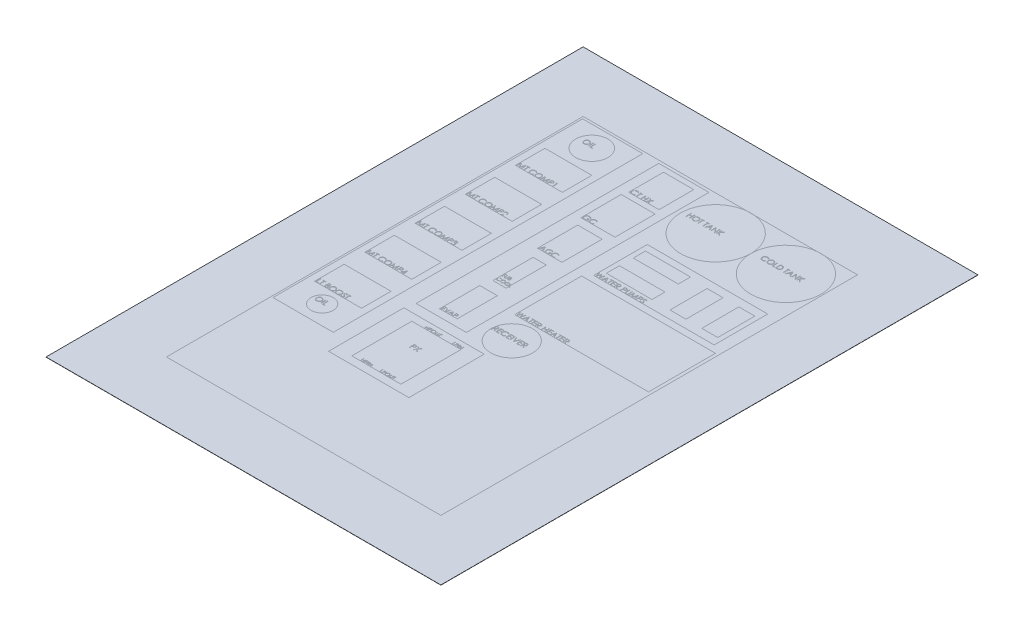
SolidWorks part; units mm, degrees
ref_plane "Front Plane" through (0, 0, 0) normal (0, 0, 1) x (1, 0, 0)
ref_plane "Top Plane" through (0, 0, 0) normal (0, 1, 0) x (1, 0, 0)
ref_plane "Right Plane" through (0, 0, 0) normal (1, 0, 0) x (0, 0, -1)
sketch "Sketch1" plane through (0, 0, 0) normal (0, 1, 0) x (1, 0, 0)
  line L1 (2997.2, 4076.7) -> (-2997.2, 4076.7)
  line L2 (2997.2, 4076.7) -> (2997.2, -4076.7)
  line L3 (2997.2, -4076.7) -> (-2997.2, -4076.7)
  line L4 (-2997.2, 4076.7) -> (-2997.2, -4076.7)
  line L5 (0, -4076.7) -> (0, 4076.7) construction
  line L6 (2997.2, 0) -> (-2997.2, 0) construction
  point P0 (0, 0)
  dimension "D1" = 5994.4
  dimension "D2" = 8153.4
extrude "Boss-Extrude1" add sketch "Sketch1" against normal blind 2.54
sketch "Sketch2" plane through (0, 0, 0) normal (0, 1, 0) x (1, 0, 0)
  line L0 (-2997.2, -4076.7) -> (2997.2, -4076.7) construction
  line L1 (-2082.8, 3162.3) -> (2082.8, 3162.3)
  line L2 (-2082.8, 3162.3) -> (-2082.8, -3162.3)
  line L3 (-2082.8, -3162.3) -> (2082.8, -3162.3)
  line L4 (2082.8, 3162.3) -> (2082.8, -3162.3)
  line L5 (0, -3162.3) -> (0, 3162.3) construction
  line L6 (-2082.8, 0) -> (2082.8, 0) construction
  line L7 (-2997.2, 4076.7) -> (-2997.2, -4076.7) construction
  point P0 (0, 0)
  dimension "D1" = 914.4
  dimension "D2" = 914.4
split line "Split Line1"
sketch "Sketch3" plane through (0, 0, 0) normal (0, 1, 0) x (1, 0, 0)
  line L0 (-1953.5274, 1244.4006) -> (-1242.3274, 1244.4006)
  line L1 (-2055.1274, 3126.5428) -> (-1140.7274, 3126.5428)
  line L2 (-2055.1274, 3126.5428) -> (-2055.1274, -1572.4572)
  line L3 (-2055.1274, -1572.4572) -> (-1140.7274, -1572.4572)
  line L4 (-1140.7274, 3126.5428) -> (-1140.7274, -1572.4572)
  line L5 (-1597.9274, -1572.4572) -> (-1597.9274, 3126.5428) construction
  line L6 (-2055.1274, 777.0428) -> (-1140.7274, 777.0428) construction
  line L7 (-1953.5274, 2006.4006) -> (-1242.3274, 2006.4006)
  line L8 (-1953.5274, 2006.4006) -> (-1953.5274, 2453.4406)
  line L9 (-1953.5274, 2453.4406) -> (-1242.3274, 2453.4406)
  line L10 (-1242.3274, 2006.4006) -> (-1242.3274, 2453.4406)
  line L11 (-1597.9274, 2453.4406) -> (-1597.9274, 2006.4006) construction
  line L12 (-1953.5274, 2229.9206) -> (-1242.3274, 2229.9206) construction
  line L13 (-1242.3274, 1244.4006) -> (-1242.3274, 1691.4406)
  line L14 (-1953.5274, 1691.4406) -> (-1242.3274, 1691.4406)
  line L15 (-1953.5274, 1244.4006) -> (-1953.5274, 1691.4406)
  line L16 (-1953.5274, 482.4006) -> (-1242.3274, 482.4006)
  line L17 (-1242.3274, 482.4006) -> (-1242.3274, 929.4406)
  line L18 (-1953.5274, 929.4406) -> (-1242.3274, 929.4406)
  line L19 (-1953.5274, 482.4006) -> (-1953.5274, 929.4406)
  line L20 (-1953.5274, -279.5994) -> (-1242.3274, -279.5994)
  line L21 (-1242.3274, -279.5994) -> (-1242.3274, 167.4406)
  line L22 (-1953.5274, 167.4406) -> (-1242.3274, 167.4406)
  line L23 (-1953.5274, -279.5994) -> (-1953.5274, 167.4406)
  line L24 (-1953.5274, -1041.5994) -> (-1242.3274, -1041.5994)
  line L29 (-927.3956, -713.9777) -> (291.8044, -713.9777)
  line L30 (-927.3956, -713.9777) -> (-927.3956, -1856.9777)
  line L35 (0, 4076.7) -> (0, -4076.7) construction
  line L36 (2387.6, 0) -> (-2387.6, 0) construction
  line L37 (-927.3956, -1856.9777) -> (291.8044, -1856.9777)
  line L38 (291.8044, -713.9777) -> (291.8044, -1856.9777)
  line L39 (-317.7956, -1856.9777) -> (-317.7956, -713.9777) construction
  line L40 (-927.3956, -1285.4777) -> (291.8044, -1285.4777) construction
  line L41 (-891.0895, 3118.7654) -> (-129.0895, 3118.7654)
  line L42 (-891.0895, 3118.7654) -> (-891.0895, -564.2346)
  line L43 (-891.0895, -564.2346) -> (-129.0895, -564.2346)
  line L44 (-129.0895, 3118.7654) -> (-129.0895, -564.2346)
  line L45 (-510.0895, -564.2346) -> (-510.0895, 3118.7654) construction
  line L46 (-891.0895, 1277.2654) -> (-129.0895, 1277.2654) construction
  line L47 (-1242.3274, -1041.5994) -> (-1242.3274, -594.5594)
  line L48 (87.4738, 1965.4605) -> (1916.2738, 1965.4605)
  line L49 (87.4738, 1965.4605) -> (87.4738, 1152.6605)
  line L50 (87.4738, 1152.6605) -> (1916.2738, 1152.6605)
  line L51 (1916.2738, 1965.4605) -> (1916.2738, 1152.6605)
  line L52 (1001.8738, 1152.6605) -> (1001.8738, 1965.4605) construction
  line L53 (87.4738, 1559.0605) -> (1916.2738, 1559.0605) construction
  line L58 (-376.8877, -1193.0963) -> (-157.3231, -1193.0963) construction
  line L59 (159.8564, 1866.0856) -> (843.3441, 1866.0856)
  line L60 (-1953.5274, -594.5594) -> (-1242.3274, -594.5594)
  line L61 (-1953.5274, -1041.5994) -> (-1953.5274, -594.5594)
  line L62 (459.9911, 2631.5365) -> (1526.7911, 2631.5365) construction
  line L64 (3.5213, 1053.0045) -> (2035.5213, 1053.0045)
  line L65 (3.5213, 1053.0045) -> (3.5213, 37.0045)
  line L66 (3.5213, 37.0045) -> (2035.5213, 37.0045)
  line L67 (2035.5213, 1053.0045) -> (2035.5213, 37.0045)
  line L68 (1019.5213, 37.0045) -> (1019.5213, 1053.0045) construction
  line L69 (3.5213, 545.0045) -> (2035.5213, 545.0045) construction
  line L70 (-739.499, 2512.3519) -> (-280.68, 2512.3519)
  line L71 (-739.499, 2512.3519) -> (-739.499, 3039.5984)
  line L72 (-739.499, 3039.5984) -> (-280.68, 3039.5984)
  line L73 (-280.68, 2512.3519) -> (-280.68, 3039.5984)
  line L74 (-510.0895, 3039.5984) -> (-510.0895, 2512.3519) construction
  line L75 (-739.499, 2775.9751) -> (-280.68, 2775.9751) construction
  line L76 (-767.4761, 1815.7784) -> (-252.7028, 1815.7784)
  line L77 (-767.4761, 1815.7784) -> (-767.4761, 2425.3784)
  line L78 (-767.4761, 2425.3784) -> (-252.7028, 2425.3784)
  line L79 (-252.7028, 1815.7784) -> (-252.7028, 2425.3784)
  line L80 (-510.0895, 2425.3784) -> (-510.0895, 1815.7784) construction
  line L81 (-767.4761, 2120.5784) -> (-252.7028, 2120.5784) construction
  line L82 (-695.4774, 1083.3993) -> (-324.7016, 1083.3993)
  line L83 (-695.4774, 1083.3993) -> (-695.4774, 1692.9993)
  line L84 (-695.4774, 1692.9993) -> (-324.7016, 1692.9993)
  line L85 (-324.7016, 1083.3993) -> (-324.7016, 1692.9993)
  line L86 (-510.0895, 1692.9993) -> (-510.0895, 1083.3993) construction
  line L87 (-695.4774, 1388.1993) -> (-324.7016, 1388.1993) construction
  line L88 (-610.5235, 320.3017) -> (-409.6555, 320.3017)
  line L89 (-610.5235, 320.3017) -> (-610.5235, 929.9017)
  line L90 (-610.5235, 929.9017) -> (-409.6555, 929.9017)
  line L91 (-409.6555, 320.3017) -> (-409.6555, 929.9017)
  line L92 (-510.0895, 929.9017) -> (-510.0895, 320.3017) construction
  line L93 (-610.5235, 625.1017) -> (-409.6555, 625.1017) construction
  line L94 (-643.2912, -454.8388) -> (-376.8877, -454.8388)
  line L95 (-643.2912, -454.8388) -> (-643.2912, 154.7612)
  line L96 (-643.2912, 154.7612) -> (-376.8877, 154.7612)
  line L97 (-376.8877, -454.8388) -> (-376.8877, 154.7612)
  line L98 (-510.0895, 154.7612) -> (-510.0895, -454.8388) construction
  line L99 (-643.2912, -150.0388) -> (-376.8877, -150.0388) construction
  line L104 (159.8564, 1866.0856) -> (159.8564, 1680.7179)
  line L105 (155.8267, 1559.0605) -> (397.9781, 1559.0605) construction
  line L109 (1363.1781, 1840.8555) -> (1363.1781, 1277.2654)
  line L110 (1121.0267, 1840.8555) -> (1363.1781, 1840.8555)
  line L111 (1121.0267, 1840.8555) -> (1121.0267, 1277.2654)
  line L112 (1121.0267, 1277.2654) -> (1363.1781, 1277.2654)
  line L113 (1845.7781, 1840.8555) -> (1845.7781, 1277.2654)
  line L114 (1603.6267, 1840.8555) -> (1845.7781, 1840.8555)
  line L115 (1603.6267, 1840.8555) -> (1603.6267, 1277.2654)
  line L116 (1603.6267, 1277.2654) -> (1845.7781, 1277.2654)
  line L117 (159.8564, 1680.7179) -> (843.3441, 1680.7179)
  line L118 (-1762.7379, 2809.6251) -> (-1419.3839, 2809.6251) construction
  line L119 (-1728.5181, -1284.3926) -> (-1493.1188, -1284.3926) construction
  line L120 (8.1371, -329.3426) -> (643.1371, -329.3426) construction
  line L121 (0, 2631.5365) -> (459.9911, 2631.5365) construction
  line L122 (1121.0267, 2631.5365) -> (1845.7781, 2631.5365) construction
  line L123 (843.3441, 1866.0856) -> (843.3441, 1680.7179)
  line L124 (55.0486, -1740.9553) -> (-690.6399, -1740.9553)
  line L125 (55.0486, -1740.9553) -> (55.0486, -830.0002)
  line L126 (55.0486, -830.0002) -> (-690.6399, -830.0002)
  line L127 (-690.6399, -1740.9553) -> (-690.6399, -830.0002)
  line L128 (-317.7956, -830.0002) -> (-317.7956, -1740.9553) construction
  line L129 (55.0486, -1285.4777) -> (-690.6399, -1285.4777) construction
  line L134 (501.6003, 1680.7179) -> (501.6003, 1866.0856) construction
  line L135 (159.8564, 1773.4018) -> (843.3441, 1773.4018) construction
  line L136 (155.8267, 1475.2016) -> (847.3738, 1475.2016)
  line L137 (155.8267, 1475.2016) -> (155.8267, 1277.2654)
  line L138 (155.8267, 1277.2654) -> (847.3738, 1277.2654)
  line L139 (847.3738, 1475.2016) -> (847.3738, 1277.2654)
  line L140 (501.6003, 1277.2654) -> (501.6003, 1475.2016) construction
  line L141 (155.8267, 1376.2335) -> (847.3738, 1376.2335) construction
  circle A0 centre (325.6371, -329.3426) radius 317.5
  circle A1 centre (1526.7911, 2631.5365) radius 533.4
  circle A2 centre (459.9911, 2631.5365) radius 533.4
  circle A3 centre (-1597.9274, 2809.6251) radius 244.3696
  circle A4 centre (-1597.9274, -1284.3926) radius 168.3871
  text T0 "MT COMP1" font "Century Gothic" height in points 300
  text T1 "MT COMP2" font "Century Gothic" height in points 300
  text T2 "MT COMP3" font "Century Gothic" height in points 300
  text T3 "MT COMP4" font "Century Gothic" height in points 300
  text T4 "LT BOOST" font "Century Gothic" height in points 300
  text T5 "OIL" font "Century Gothic" height in points 300
  text T6 "OIL" font "Century Gothic" height in points 300
  text T7 "CT HX" font "Century Gothic" height in points 300
  text T8 "GC" font "Century Gothic" height in points 300
  text T9 "AGC" font "Century Gothic" height in points 300
  text T10 "\r\n\r\nSUB\r\nCOOL" font "Century Gothic" height in points 200
  text T11 "EVAP" font "Century Gothic" height in points 250
  text T12 "RECEIVER" font "Century Gothic" height in points 300
  text T13 "HOT TANK" font "Century Gothic" height in points 300
  text T14 "COLD TANK" font "Century Gothic" height in points 300
  text T15 "WATER HEATER" font "Century Gothic" height in points 300
  text T16 "WATER PUMPS" font "Century Gothic" height in points 300
  text T17 "HPOUT         LPIN" font "Century Gothic" height in points 200
  text T18 "    HPIN      LPOUT    " font "Century Gothic" height in points 200
  text T19 "PX" font "Century Gothic" height in points 300
  point P0 (-1597.9274, 777.0428)
  point P4 (0, 0)
  point P6 (-1597.9274, 2229.9206)
  point P21 (-317.7956, -1285.4777)
  point P26 (-510.0895, 1277.2654)
  point P40 (1001.8738, 1559.0605)
  point P45 (-510.0895, 2120.5784)
  point P53 (-510.0895, 1388.1993)
  point P59 (-510.0895, 625.1017)
  point P72 (276.9024, 1559.0605)
  point P74 (-510.0895, 2775.9751)
  point P93 (-376.8877, -1193.0963)
  point P96 (-510.0895, -150.0388)
  point P110 (-317.7956, -1285.4777)
  point P143 (1019.5213, 545.0045)
  point P206 (501.6003, 1376.2335)
  point P337 (501.6003, 1773.4018)
  dimension "D11" = 635
  dimension "D12" = 1066.8
  dimension "D1" = 914.4
  dimension "D2" = 4699
  dimension "D3" = 711.2
  dimension "D5" = 673.1022
  dimension "D6" = 314.96
  dimension "D7" = 1219.2
  dimension "D8" = 1143
  dimension "D9" = 762
  dimension "D10" = 3683
  dimension "D13" = 812.8
  dimension "D14" = 1828.8
  dimension "D15" = 116.0224
  dimension "D16" = 745.6885
  dimension "D17" = 2032
  dimension "D18" = 1016
  dimension "D19" = 609.6
  dimension "D4" = 5
split line "Split Line3"
